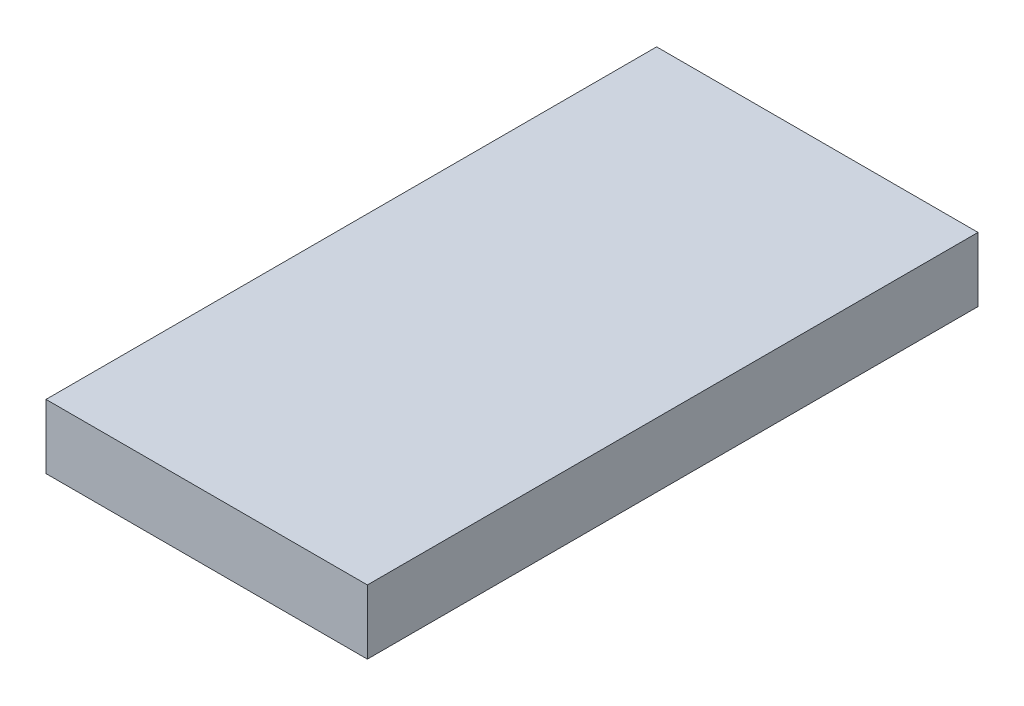
SolidWorks part; units mm, degrees
ref_plane "Plan de face" through (0, 0, 0) normal (0, 0, 1) x (1, 0, 0)
ref_plane "Plan de dessus" through (0, 0, 0) normal (0, 1, 0) x (1, 0, 0)
ref_plane "Plan de droite" through (0, 0, 0) normal (1, 0, 0) x (0, 0, -1)
sketch "Esquisse2" plane through (0, 0, 0) normal (0, 1, 0) x (1, 0, 0)
  line L1 (-20.2071, 9.6626) -> (79.7929, 9.6626)
  line L2 (-20.2071, 9.6626) -> (-20.2071, -180.3374)
  line L3 (-20.2071, -180.3374) -> (79.7929, -180.3374)
  line L4 (79.7929, 9.6626) -> (79.7929, -180.3374)
  dimension "D1" = 100
  dimension "D2" = 190
extrude "Boss.-Extru.1" add sketch "Esquisse2" along normal blind 20
